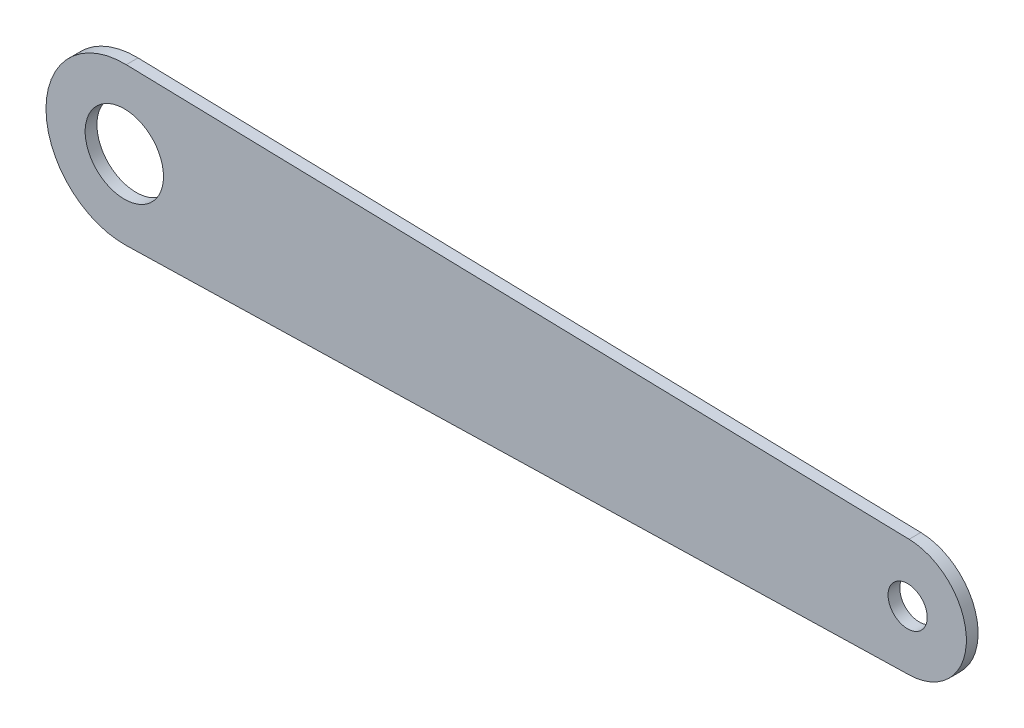
SolidWorks part; units mm, degrees
material "Acrylic (Medium-high impact)"
ref_plane "Front Plane" through (0, 0, 0) normal (0, 0, 1) x (1, 0, 0)
ref_plane "Top Plane" through (0, 0, 0) normal (0, 1, 0) x (1, 0, 0)
ref_plane "Right Plane" through (0, 0, 0) normal (1, 0, 0) x (0, 0, -1)
sketch "Sketch1" plane through (0, 0, 0) normal (0, 0, 1) x (1, 0, 0)
  line L0 (0, 0) -> (200, 0) construction
  line L3 (0.5, 19.9937) -> (200.375, 14.9953)
  line L4 (200.375, -14.9953) -> (0.5, -19.9937)
  arc A0 (0.5, 19.9937) -> (0.5, -19.9937) centre (0, 0) ccw
  arc A1 (200.375, -14.9953) -> (200.375, 14.9953) centre (200, 0) ccw
  circle A2 centre (0, 0) radius 10
  circle A3 centre (200, 0) radius 5
  point P3 (10, 0)
  dimension "D2" = 20
  dimension "D3" = 10
  dimension "D1" = 10
  dimension "D4" = 10
  dimension "D5" = 200
extrude "Boss-Extrude1" add sketch "Sketch1" along normal blind 3
